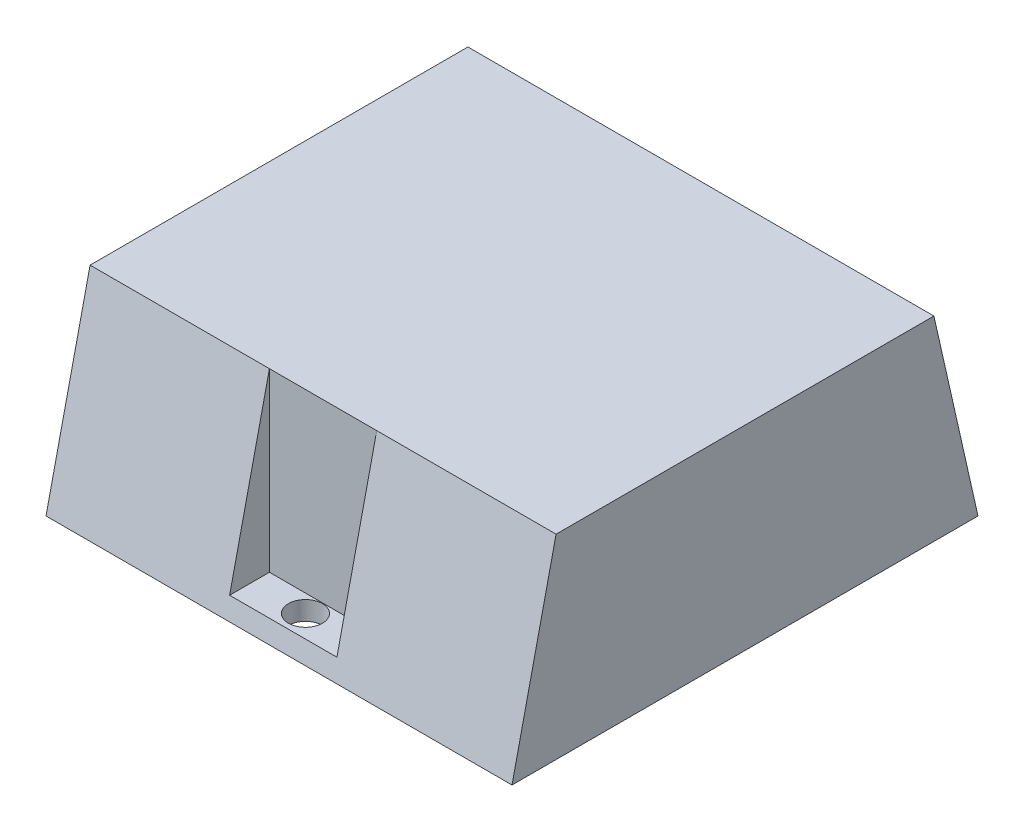
SolidWorks part; units mm, degrees
ref_plane "前视基准面" through (0, 0, 0) normal (0, 0, 1) x (1, 0, 0)
ref_plane "上视基准面" through (0, 0, 0) normal (0, 1, 0) x (1, 0, 0)
ref_plane "右视基准面" through (0, 0, 0) normal (1, 0, 0) x (0, 0, -1)
other "Configuration Table"
sketch "草图1" plane through (0, 0, 0) normal (0, 1, 0) x (1, 0, 0)
  line L1 (37, -37) -> (-37, -37)
  line L2 (37, -37) -> (37, 37)
  line L3 (37, 37) -> (-37, 37)
  line L4 (-37, -37) -> (-37, 37)
  line L5 (37, -37) -> (-37, 37) construction
  line L6 (37, 37) -> (-37, -37) construction
  point P0 (0, 0)
  dimension "D1" = 74
  dimension "D2" = 74
extrude "凸台-拉伸1" add sketch "草图1" along normal blind 31
sketch "草图2" plane through (-37, 0, 0) normal (-1, 0, 0) x (0, 0, 1)
  line L0 (30, 31) -> (-30, 31)
  line L1 (-37, 31) -> (37, 31) construction
  line L2 (-30, 31) -> (-37, 0)
  line L3 (30, 31) -> (37, 0)
  line L4 (37, 0) -> (-37, 0)
  point P5 (0, 31)
  dimension "D1" = 60
extrude "切除-拉伸1" cut sketch "草图2" against normal through all flip side to cut
sketch "草图3" plane through (-37, 0, 0) normal (-1, 0, 0) x (0, 0, 1)
  line L0 (-37, 0) -> (37, 0) construction
  line L1 (15.7748, 15.3494) -> (-15.7748, 15.3494)
  line L2 (15.7748, 15.3494) -> (15.7748, 0)
  line L3 (15.7748, 0) -> (-15.7748, 0)
  line L4 (-15.7748, 15.3494) -> (-15.7748, 0)
  line L5 (15.7748, 15.3494) -> (-15.7748, 0) construction
  line L6 (15.7748, 0) -> (-15.7748, 15.3494) construction
  point P0 (0, 7.6747)
extrude "凸台-拉伸2" add sketch "草图3" along normal blind 3
sketch "草图4" plane through (0, 31, 0) normal (0, 1, 0) x (1, 0, 0)
  line L0 (37, 30) -> (-37, 30) construction
  line L1 (-8.5194, 30) -> (8.5194, 30)
  line L2 (-8.5194, 30) -> (-8.5194, 37)
  line L3 (-8.5194, 37) -> (8.5194, 37)
  line L4 (8.5194, 30) -> (8.5194, 37)
  line L5 (37, 37) -> (-37, 37) construction
  line L6 (-37, -37) -> (37, -37) construction
  line L7 (-8.5194, -37) -> (8.5194, -37)
  line L8 (-8.5194, -37) -> (-8.5194, -30)
  line L9 (-8.5194, -30) -> (8.5194, -30)
  line L10 (8.5194, -37) -> (8.5194, -30)
  line L11 (37, -30) -> (-37, -30) construction
  line L12 (-8.5194, 37) -> (8.5194, 30)
  line L13 (8.5194, 37) -> (-8.5194, 30)
  line L14 (-8.5194, -30) -> (8.5194, -37)
  line L15 (8.5194, -30) -> (-8.5194, -37)
  point P16 (0, -33.5)
  point P17 (0, 33.5)
  line M10 (37, 30) -> (-37, 30)
  line M12 (-37, -30) -> (37, -30)
extrude "切除-拉伸2" cut sketch "草图4" against normal blind 28 contours L13 L3 L12 | L13 L12 L2 | L4 L13 L12 | L12 L13 M10 | L15 L14 L8 | L14 L15 L7 | L10 L15 L14 | L15 L14 M12
sketch "草图6" plane through (0, 3, 0) normal (0, 1, 0) x (1, 0, 0)
  line L1 (-37, 0) -> (37, 0) construction
  line L2 (-37, 30) -> (-37, -30) construction
  line L3 (37, -30) -> (37, 30) construction
  circle A0 centre (0, -32.8) radius 2.7
  circle A1 centre (0, 32.8) radius 2.7
  point P6 (0, 0)
  dimension "D1" = 65.6
extrude "切除-拉伸4" cut sketch "草图6" against normal blind 28 contours A0 | A1
